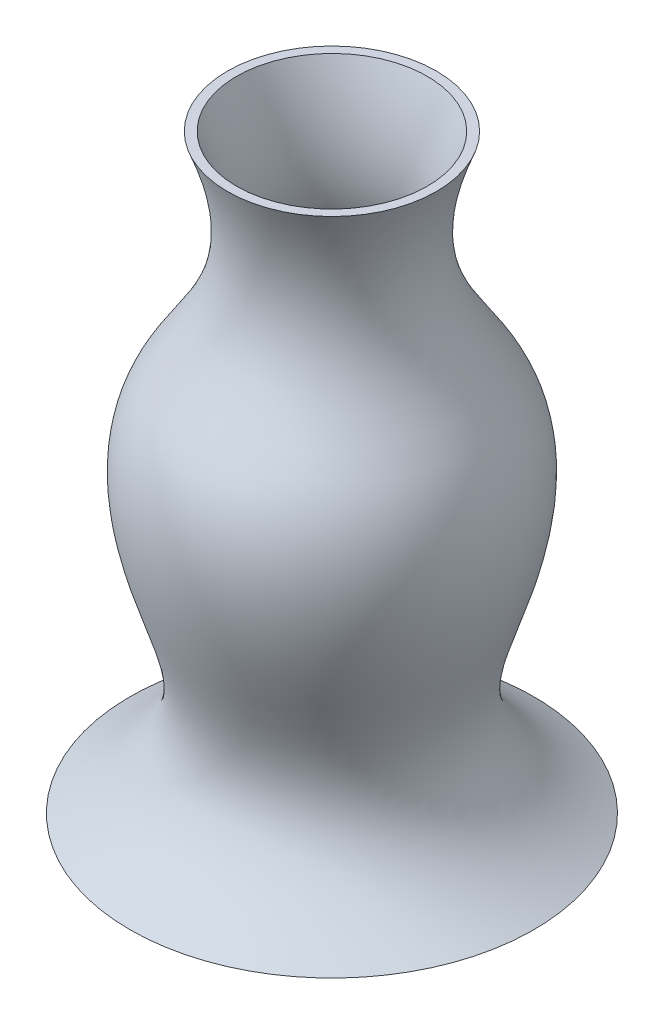
SolidWorks part; units mm, degrees
ref_plane "Front Plane" through (0, 0, 0) normal (0, 0, 1) x (1, 0, 0)
ref_plane "Top Plane" through (0, 0, 0) normal (0, 1, 0) x (1, 0, 0)
ref_plane "Right Plane" through (0, 0, 0) normal (1, 0, 0) x (0, 0, -1)
sketch "Sketch1" plane through (0, 0, 0) normal (0, 0, 1) x (1, 0, 0)
  line L0 (0, 23.5387) -> (0, -81.0695) construction
  line L1 (18.4973, 23.5387) -> (0, 23.5387)
  line L2 (35.765, -81.0695) -> (0, -81.0695)
  line L3 (0, 23.5387) -> (0, -81.0695)
  spline S0 degree 3 poles (18.4973, 23.5387) (9.7144, 1.5782) (31.7091, -15.1333) (26.0712, -48.2339) (14.973, -69.7007) (35.765, -81.0695) knots 0 0 0 0 0.292877 0.612997 1 1 1 1
  point P5 (22.9978, -12.0105)
  point P7 (20.2481, -71.281)
  point P9 (31.5523, 50.3151)
  point P11 (60.5765, -92.3617)
  point P12 (27.5806, -55.0886)
  point P13 (23.3033, -41.6458)
  point P14 (37.4896, -43.7195)
  point P15 (50.824, -89.7805)
  point P16 (33.2367, -49.0724)
  point P17 (21.0573, -60.6119)
  point P18 (24.9908, -45.6226)
  point P19 (18.4973, 23.5387)
  point P20 (35.765, -81.0695)
revolve "Revolve1" add sketch "Sketch1" angle 360 about L3
shell "Shell1" thickness 1.5
